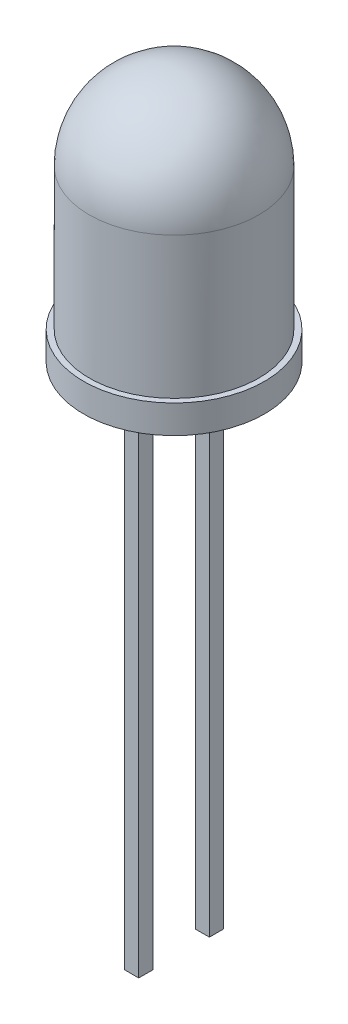
SolidWorks part; units mm, degrees
material "Acrylic (Medium-high impact)"
ref_plane "Front Plane" through (0, 0, 0) normal (0, 0, 1) x (1, 0, 0)
ref_plane "Top Plane" through (0, 0, 0) normal (0, 1, 0) x (1, 0, 0)
ref_plane "Right Plane" through (0, 0, 0) normal (1, 0, 0) x (0, 0, -1)
sketch "Sketch1" plane through (0, 0, 0) normal (0, 0, 1) x (1, 0, 0)
  line L0 (-3, 0) -> (-3, 5)
  line L1 (-3, 0) -> (0, 0)
  line L2 (0, 0) -> (0, 5)
  line L3 (0, 5) -> (0, 8)
  arc A0 (0, 8) -> (-3, 5) centre (0, 5) ccw
  dimension "D1" = 3
  dimension "D2" = 5
  dimension "D3" = 3
revolve "Revolve1" add sketch "Sketch1" angle 360 about L2
sketch "Sketch2" plane through (0, 0, 0) normal (0, -1, 0) x (-1, 0, 0)
  circle A0 centre (0, 0) radius 3.2
extrude "Boss-Extrude1" add sketch "Sketch2" along normal blind 1
sketch "Sketch3" plane through (0, -1, 0) normal (0, -1, 0) x (-1, 0, 0)
  line L1 (0.25, -1.5) -> (-0.25, -1.5)
  line L2 (0.25, -1.5) -> (0.25, -1)
  line L3 (0.25, -1) -> (-0.25, -1)
  line L4 (-0.25, -1.5) -> (-0.25, -1)
  dimension "D1" = 0.25
  dimension "D2" = 0.5
  dimension "D3" = 0.5
  dimension "D4" = 1
extrude "Boss-Extrude2" add sketch "Sketch3" along normal blind 18
mirror "Mirror1" about plane through (0, 0, 0) normal (0, 0, 1) of "Boss-Extrude2"
